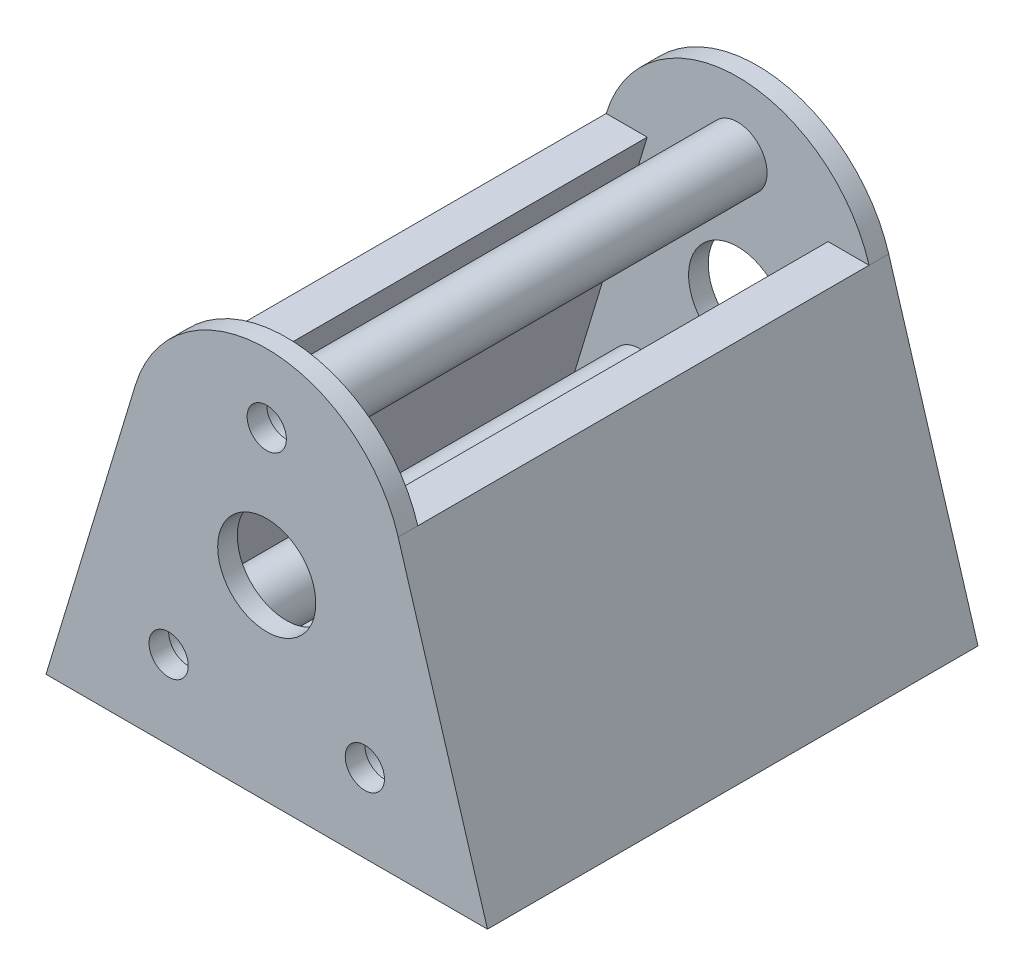
SolidWorks part; units mm, degrees
ref_plane "Front Plane" through (0, 0, 0) normal (0, 0, 1) x (1, 0, 0)
ref_plane "Top Plane" through (0, 0, 0) normal (0, 1, 0) x (1, 0, 0)
ref_plane "Right Plane" through (0, 0, 0) normal (1, 0, 0) x (0, 0, -1)
sketch "Sketch1" plane through (0, 0, 0) normal (0, 0, 1) x (1, 0, 0)
  line L0 (-22.5, 0) -> (22.5, 0)
  line L1 (0, 0) -> (0, 40) construction
  line L2 (22.5, 0) -> (13.3993, 30.0571)
  line L3 (-22.5, 0) -> (-13.3993, 30.0571)
  line L4 (-10, 8) -> (10, 8) construction
  arc A0 (13.3993, 30.0571) -> (-13.3993, 30.0571) centre (0, 26) ccw
  circle A1 centre (0, 20) radius 5
  circle A2 centre (0, 33) radius 2
  circle A3 centre (10, 8) radius 2
  circle A4 centre (-10, 8) radius 2
  point P4 (0, 0)
  point P20 (0, 8)
  dimension "D3" = 28
  dimension "D4" = 10
  dimension "D5" = 7
  dimension "D6" = 4
  dimension "D7" = 4
  dimension "D8" = 20
  dimension "D1" = 45
  dimension "D2" = 40
  dimension "D9" = 8
extrude "Boss-Extrude1" add sketch "Sketch1" along normal blind 2
ref_plane "Plane1" through (0, 0, 50) normal (0, 0, -1) x (-1, 0, 0)
sketch "Sketch2" plane through (0, 0, 50) normal (0, 0, -1) x (-1, 0, 0)
  line L3 (-13.3993, 30.0571) -> (-22.5, 0)
  line L4 (22.5, 0) -> (13.3993, 30.0571)
  line L5 (-22.5, 0) -> (22.5, 0)
  line L6 (-13.3993, 30.0571) -> (-22.5, 0)
  line L7 (22.5, 0) -> (13.3993, 30.0571)
  line L8 (-22.5, 0) -> (22.5, 0)
  circle A0 centre (-10, 8) radius 2 construction
  arc A1 (13.3993, 30.0571) -> (-13.3993, 30.0571) centre (0, 26) ccw
  arc A2 (13.3993, 30.0571) -> (-13.3993, 30.0571) centre (0, 26) ccw
  circle A3 centre (10, 8) radius 2 construction
  circle A4 centre (0, 20) radius 5 construction
  circle A5 centre (-10, 8) radius 2
  circle A6 centre (10, 8) radius 2
  circle A7 centre (0, 20) radius 5
  circle A8 centre (0, 33) radius 2 construction
  circle A9 centre (0, 33) radius 2
  dimension "D1" = 0
extrude "Boss-Extrude2" add sketch "Sketch2" along normal blind 2 separate body
sketch "Sketch3" plane through (0, 0, 48) normal (0, 0, -1) x (-1, 0, 0)
  line L0 (0, 0) -> (0, 21.0876) construction
  line L1 (-22.5, 0) -> (22.5, 0) construction
  circle A1 centre (10, 8) radius 3
  circle A2 centre (10, 8) radius 2.5
  circle A3 centre (0, 33) radius 3
  circle A4 centre (0, 33) radius 2.5
  circle A5 centre (-10, 8) radius 2.5
  circle A6 centre (-10, 8) radius 3
  dimension "D1" = 6
  dimension "D3" = 6
  dimension "D2" = 0.5
  dimension "D4" = 0.5
extrude "Boss-Extrude3" add sketch "Sketch3" along normal up to surface (46 mm away) up to face at (12, 8, 2)
sketch "Sketch4" plane through (0, 0, 48) normal (0, 0, -1) x (-1, 0, 0)
  line L0 (-13.3993, 30.0571) -> (-22.5, 0) construction
  line L1 (22.5, 0) -> (-22.5, 0)
  line L3 (21.2889, 4) -> (-21.2889, 4)
  line L5 (22.5, 0) -> (21.2889, 4)
  line L6 (22.5, 0) -> (13.3993, 30.0571) construction
  line L7 (-22.5, 0) -> (-21.2889, 4)
  dimension "D1" = 4
extrude "Boss-Extrude4" add sketch "Sketch4" along normal up to surface (46 mm away) up to face at (13, 8, 2)
sketch "Sketch5" plane through (0, 0, 48) normal (0, 0, -1) x (-1, 0, 0)
  line L0 (21.2889, 4) -> (13.3993, 30.0571) construction
  line L1 (21.2889, 4) -> (13.3993, 30.0571)
  line L2 (17.4605, 2.8408) -> (9.2199, 30.0571)
  line L3 (21.2889, 4) -> (17.1095, 4)
  line L4 (21.2889, 4) -> (-21.2889, 4) construction
  line L5 (13.3993, 30.0571) -> (9.2199, 30.0571)
  line L6 (17.4605, 2.8408) -> (9.5709, 28.8979) construction
  line L7 (0, 0) -> (0, 26.3522) construction
  line L8 (-21.2889, 4) -> (-17.1095, 4)
  line L9 (-21.2889, 4) -> (-13.3993, 30.0571)
  line L10 (-13.3993, 30.0571) -> (-9.2199, 30.0571)
  line L11 (-17.4605, 2.8408) -> (-9.2199, 30.0571)
  line M10 (-13.3993, 30.0571) -> (-21.2889, 4)
  line M11 (-21.2889, 4) -> (21.2889, 4)
  line M12 (21.2889, 4) -> (13.3993, 30.0571)
  dimension "D1" = 4
extrude "Boss-Extrude5" add sketch "Sketch5" along normal up to surface (46 mm away) contours L5 L2 M12 M11 | L11 L10 M11 M10 up to face at (13, 8, 2)
sketch "Sketch6" plane through (0, 0, 50) normal (0, 0, -1) x (-1, 0, 0)
  circle A0 centre (0, 20) radius 2.5581
ref_plane "Plane2" through (0, 20, 0) normal (0, 1, 0) x (1, 0, 0)
sketch "Sketch7" plane through (0, 20, 0) normal (0, 1, 0) x (1, 0, 0)
  line L0 (0, 0) -> (0, -25) construction
sketch "Sketch8" plane through (0, 0, 0) normal (0, -1, 0) x (1, 0, 0)
  line L0 (0, 0) -> (0, 50) construction
  line L1 (-2.5581, 50) -> (2.5581, 50) construction
  line L2 (0, 25) -> (-22.5, 25) construction
  line L3 (-22.5, 50) -> (-22.5, 0) construction
  line L4 (-11.25, 25) -> (-11.25, 0) construction
  line L5 (-22.5, 0) -> (22.5, 0) construction
  circle A0 centre (-11.25, 12.5) radius 5
  circle A1 centre (-11.25, 12.5) radius 2.5
  circle A2 centre (-11.25, 37.5) radius 2.5
  circle A3 centre (-11.25, 37.5) radius 5
  circle A4 centre (11.25, 37.5) radius 2.5
  circle A5 centre (11.25, 37.5) radius 5
  circle A6 centre (11.25, 12.5) radius 2.5
  circle A7 centre (11.25, 12.5) radius 5
  dimension "D1" = 10
  dimension "D2" = 5
extrude "Boss-Extrude6" add sketch "Sketch8" along normal blind 5
